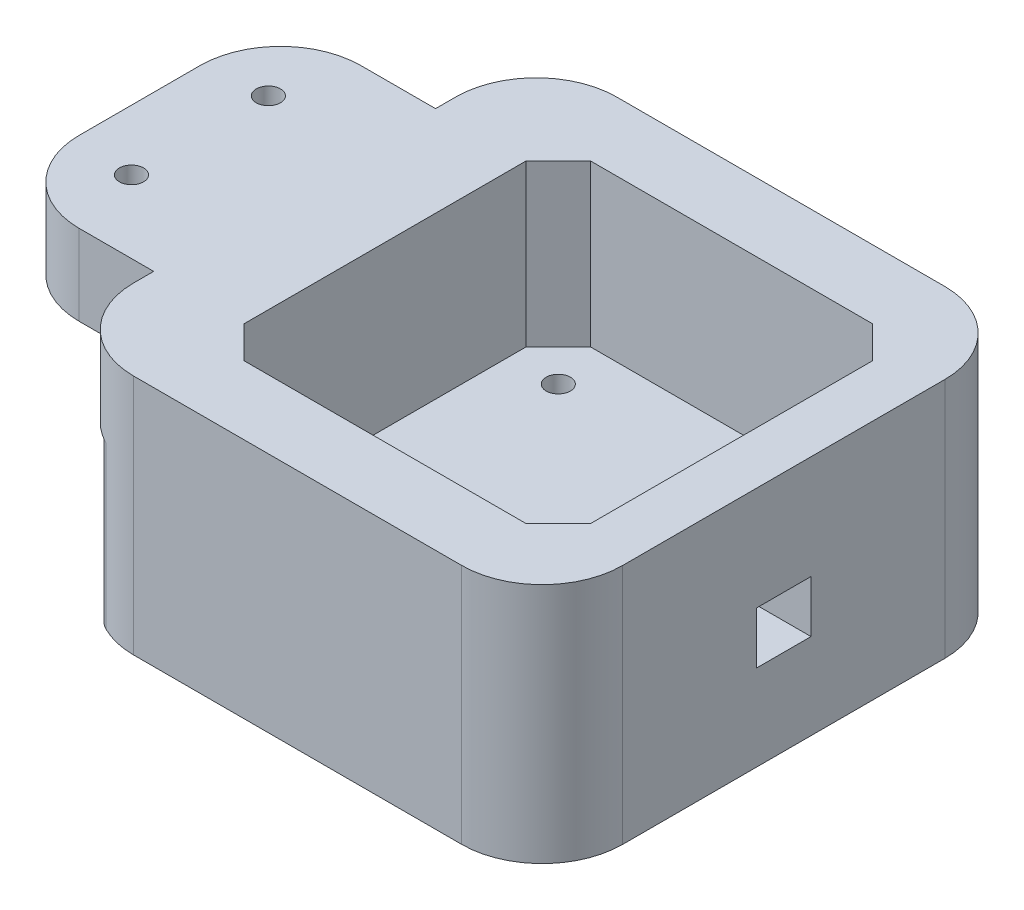
SolidWorks part; units mm, degrees
ref_plane "Front Plane" through (0, 0, 0) normal (0, 0, 1) x (1, 0, 0)
ref_plane "Top Plane" through (0, 0, 0) normal (0, 1, 0) x (1, 0, 0)
ref_plane "Right Plane" through (0, 0, 0) normal (1, 0, 0) x (0, 0, -1)
sketch "Sketch1" plane through (0, 0, 0) normal (0, 1, 0) x (1, 0, 0)
  line L1 (-40, 30) -> (40, 30)
  line L2 (-40, 30) -> (-40, -30)
  line L3 (-40, -30) -> (40, -30)
  line L4 (40, 30) -> (40, -30)
  line L5 (-40, 30) -> (40, -30) construction
  line L6 (-40, -30) -> (40, 30) construction
  point P0 (0, 0)
extrude "Boss-Extrude1" add sketch "Sketch1" along normal blind 30
fillet "Fillet1" radius 10 2 edges at (40, 15, -30) (40, 15, 30)
sketch "Sketch2" plane through (0, 30, 0) normal (0, 1, 0) x (1, 0, 0)
  line L0 (40, -20) -> (40, 20) construction
  line L1 (-11.3768, 23.3768) -> (35.3768, 23.3768) construction
  line L2 (-11.3768, 23.3768) -> (-11.3768, -23.3768) construction
  line L3 (-11.3768, -23.3768) -> (35.3768, -23.3768) construction
  line L4 (35.3768, 23.3768) -> (35.3768, -23.3768) construction
  line L5 (-11.3768, 23.3768) -> (35.3768, -23.3768) construction
  line L6 (-11.3768, -23.3768) -> (35.3768, 23.3768) construction
  line L8 (-3.5, 15.5) -> (27.5, 15.5) construction
  line L9 (-3.5, 15.5) -> (-3.5, -15.5) construction
  line L10 (-3.5, -15.5) -> (27.5, -15.5) construction
  line L11 (27.5, 15.5) -> (27.5, -15.5) construction
  line L12 (-3.5, 15.5) -> (27.5, -15.5) construction
  line L13 (-3.5, -15.5) -> (27.5, 15.5) construction
  circle A0 centre (-3.5, 15.5) radius 1.5
  circle A1 centre (27.5, 15.5) radius 1.5
  circle A2 centre (-3.5, -15.5) radius 1.5
  circle A3 centre (27.5, -15.5) radius 1.5
  point P0 (12, 0)
  point P9 (12, 0)
  dimension "D1" = 28
extrude "Cut-Extrude1" cut sketch "Sketch2" against normal through all
sketch "Sketch3" plane through (0, 30, 0) normal (0, 1, 0) x (1, 0, 0)
  line L0 (-3.5, 15.5) -> (27.5, -15.5) construction
  line L1 (-9.5, 17.5) -> (-5.5, 21.5)
  line L2 (-5.5, 21.5) -> (29.5, 21.5)
  line L3 (-9.5, 17.5) -> (-9.5, -17.5)
  line L4 (-5.5, -21.5) -> (29.5, -21.5)
  line L5 (33.5, 17.5) -> (33.5, -17.5)
  line L6 (-9.5, 21.5) -> (33.5, -21.5) construction
  line L7 (-9.5, -21.5) -> (33.5, 21.5) construction
  line L8 (29.5, 21.5) -> (33.5, 17.5)
  line L9 (-9.5, -17.5) -> (-5.5, -21.5)
  line L10 (29.5, -21.5) -> (33.5, -17.5)
  point P4 (12, 0)
  dimension "D1" = 43
extrude "Cut-Extrude2" cut sketch "Sketch3" against normal blind 20
sketch "Sketch4" plane through (0, 30, 0) normal (0, 1, 0) x (1, 0, 0)
  line L0 (-32.5, 8.5) -> (-32.5, -8.5) construction
  line L1 (-9.5, 17.5) -> (-9.5, -17.5) construction
  line L2 (-34.5, 12.5) -> (-14.5, 12.5) construction
  line L3 (-34.5, 12.5) -> (-34.5, -12.5) construction
  line L4 (-34.5, -12.5) -> (-14.5, -12.5) construction
  line L5 (-14.5, 12.5) -> (-14.5, -12.5) construction
  line L6 (-34.5, 12.5) -> (-14.5, -12.5) construction
  line L7 (-34.5, -12.5) -> (-14.5, 12.5) construction
  circle A0 centre (-32.5, 8.5) radius 1.5
  circle A1 centre (-32.5, -8.5) radius 1.5
  point P0 (-24.5, 0)
  point P3 (-32.5, 0)
  dimension "D1" = 2
  dimension "D2" = 5
extrude "Cut-Extrude3" cut sketch "Sketch4" against normal through all and the other way through all
sketch "Sketch7" plane through (0, 30, 0) normal (0, 1, 0) x (1, 0, 0)
  line L0 (-20.7447, 30) -> (-20.7447, 17.5)
  line L1 (-20.7447, 17.5) -> (-40, 17.5)
  line L2 (-20.7447, -17.5) -> (-40, -17.5)
  line L3 (-20.7447, -17.5) -> (-20.7447, -30)
  line L4 (40, -20) -> (40, 20)
  line L5 (30, 30) -> (-40, 30)
  line L6 (-40, 30) -> (-40, -30)
  line L7 (-40, -30) -> (30, -30)
  line L9 (-20.7447, 30) -> (-40, 30)
  line L10 (-40, 30) -> (-40, 17.5)
  line L11 (-40, -30) -> (-20.7447, -30)
  line L12 (-40, -17.5) -> (-40, -30)
  arc A2 (40, 20) -> (30, 30) centre (30, 20) ccw
  arc A3 (30, -30) -> (40, -20) centre (30, -20) ccw
  dimension "D1" = 0
extrude "Cut-Extrude5" cut sketch "Sketch7" against normal through all
fillet "Fillet2" radius 10 4 edges at (-40, 15, -17.5) (-20.7447, 15, -30) (-40, 15, 17.5) (-20.7447, 15, 30)
sketch "Sketch8" plane through (0, 0, 0) normal (0, -1, 0) x (1, 0, 0)
  line L0 (-17.4262, 27.4402) -> (-17.4262, -27.4402)
  line L6 (-40, 7.5) -> (-40, -7.5)
  line L7 (-30, -17.5) -> (-20.7447, -17.5)
  line L8 (-10.7447, -30) -> (30, -30)
  line L9 (40, -20) -> (40, 20)
  line L10 (30, 30) -> (-10.7447, 30)
  line L11 (-20.7447, 17.5) -> (-30, 17.5)
  line L12 (-40, 7.5) -> (-40, -7.5)
  line L13 (-30, -17.5) -> (-20.7447, -17.5)
  line L17 (-20.7447, 17.5) -> (-30, 17.5)
  line L21 (-20.7447, -17.5) -> (-20.7447, -20)
  line L22 (-20.7447, -17.5) -> (-20.7447, -20)
  line L23 (-20.7447, 20) -> (-20.7447, 17.5)
  line L24 (-20.7447, 20) -> (-20.7447, 17.5)
  arc A8 (-40, -7.5) -> (-30, -17.5) centre (-30, -7.5) ccw
  arc A10 (-20.7447, -20) -> (-10.7447, -30) centre (-10.7447, -20) ccw
  arc A11 (30, -30) -> (40, -20) centre (30, -20) ccw
  arc A12 (40, 20) -> (30, 30) centre (30, 20) ccw
  arc A13 (-10.7447, 30) -> (-20.7447, 20) centre (-10.7447, 20) ccw
  arc A15 (-30, 17.5) -> (-40, 7.5) centre (-30, 7.5) ccw
  arc A16 (-40, -7.5) -> (-30, -17.5) centre (-30, -7.5) ccw
  arc A18 (-20.7447, -20) -> (-17.4262, -27.4402) centre (-10.7447, -20) ccw
  arc A21 (-17.4262, 27.4402) -> (-20.7447, 20) centre (-10.7447, 20) ccw
  arc A23 (-30, 17.5) -> (-40, 7.5) centre (-30, 7.5) ccw
  dimension "D1" = 0
extrude "Cut-Extrude6" cut sketch "Sketch8" against normal blind 20
fillet "Fillet4" radius 4 2 edges at (-17.4262, 10, 27.4402) (-17.4262, 10, -27.4402)
sketch "Sketch9" plane through (33.5, 0, 0) normal (-1, 0, 0) x (0, 0, 1)
  line L1 (-3.3795, 17.118) -> (3.3795, 17.118)
  line L2 (-3.3795, 17.118) -> (-3.3795, 10.6592)
  line L3 (-3.3795, 10.6592) -> (3.3795, 10.6592)
  line L4 (3.3795, 17.118) -> (3.3795, 10.6592)
  line L5 (-3.3795, 17.118) -> (3.3795, 10.6592) construction
  line L6 (-3.3795, 10.6592) -> (3.3795, 17.118) construction
  point P0 (0, 13.8886)
extrude "Cut-Extrude7" cut sketch "Sketch9" against normal through all
